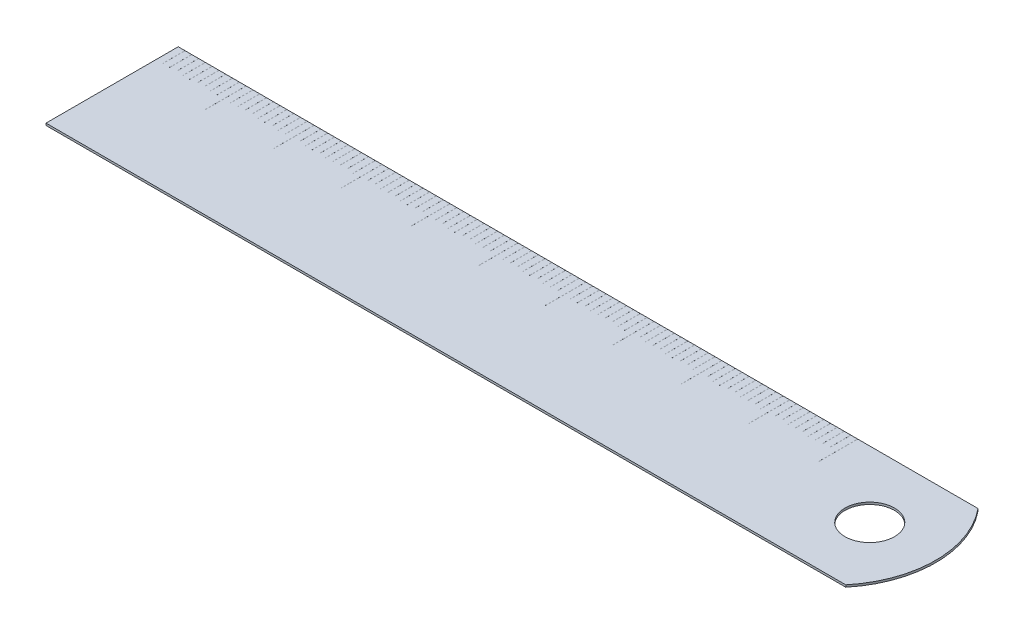
SolidWorks part; units mm, degrees
ref_plane "前视基准面" through (0, 0, 0) normal (0, 0, 1) x (1, 0, 0)
ref_plane "上视基准面" through (0, 0, 0) normal (0, 1, 0) x (1, 0, 0)
ref_plane "右视基准面" through (0, 0, 0) normal (1, 0, 0) x (0, 0, -1)
other "Configuration Table"
sketch "草图1" plane through (0, 0, 0) normal (0, 1, 0) x (1, 0, 0)
  line L0 (54.55, 33.5841) -> (54.55, -41.4159) construction
  line L1 (60.6, -9.73) -> (-60.6, -9.73)
  line L2 (60.6, -9.73) -> (60.6, 9.73)
  line L3 (60.6, 9.73) -> (-60.6, 9.73)
  line L4 (-60.6, -9.73) -> (-60.6, 9.73)
  line L5 (60.6, -9.73) -> (-60.6, 9.73) construction
  line L6 (60.6, 9.73) -> (-60.6, -9.73) construction
  line L7 (57.1, 22.1246) -> (57.1, -27.5081) construction
  circle A0 centre (50.9, 0) radius 3.65
  arc A3 (57.1, -9.73) -> (57.1, 9.73) centre (45.3253, 0) ccw
  point P0 (0, 0)
  point P17 (57.1, 9.73)
  dimension "D4" = 7.3
  dimension "D1" = 121.2
  dimension "D2" = 19.46
  dimension "D3" = 6.05
  dimension "D5" = 117.7
extrude "凸台-拉伸1" add sketch "草图1" along normal blind 0.31 contours L1 A3 L3 L4 A0
sketch "草图2" plane through (0, 0.31, 0) normal (0, 1, 0) x (1, 0, 0)
  line L0 (57.1, 9.73) -> (-60.6, 9.73) construction
  line L1 (-50.61, 15.73) -> (-50.59, 15.73)
  line L2 (-50.61, 15.73) -> (-50.61, 3.73)
  line L3 (-50.61, 3.73) -> (-50.59, 3.73)
  line L4 (-50.59, 15.73) -> (-50.59, 3.73)
  line L5 (-50.61, 15.73) -> (-50.59, 3.73) construction
  line L6 (-50.61, 3.73) -> (-50.59, 15.73) construction
  line L7 (-60.6, -9.73) -> (-60.6, 9.73) construction
  point P0 (-50.6, 9.73)
  dimension "D1" = 10
  dimension "D2" = 0.02
  dimension "D3" = 6
extrude "切除-拉伸1" cut sketch "草图2" against normal blind 0.002
pattern_linear "阵列(线性)1" count 10 spacing 10 along (1, 0, 0) of "切除-拉伸1"
ref_plane "基准面2" through (0, 0.155, 0) normal (0, -1, 0) x (-1, 0, 0)
sketch "草图3" plane through (0, 0.31, 0) normal (0, 1, 0) x (1, 0, 0)
  line L0 (-50.61, 9.73) -> (-60.6, 9.73) construction
  line L1 (-59.61, 6.43) -> (-59.59, 6.43)
  line L2 (-59.61, 6.43) -> (-59.61, 13.03)
  line L3 (-59.61, 13.03) -> (-59.59, 13.03)
  line L4 (-59.59, 6.43) -> (-59.59, 13.03)
  line L5 (-59.61, 6.43) -> (-59.59, 13.03) construction
  line L6 (-59.61, 13.03) -> (-59.59, 6.43) construction
  line L7 (-60.6, -9.73) -> (-60.6, 9.73) construction
  point P0 (-59.6, 9.73)
  dimension "D1" = 3.3
  dimension "D2" = 1
  dimension "D3" = 0.02
extrude "切除-拉伸3" cut sketch "草图3" against normal blind 0.002
pattern_linear "阵列(线性)2" count 9 spacing 1 along (1, 0, 0) of "切除-拉伸3"
pattern_linear "阵列(线性)3" count 10 spacing 10 along (1, 0, 0) of "切除-拉伸3", "阵列(线性)2"
